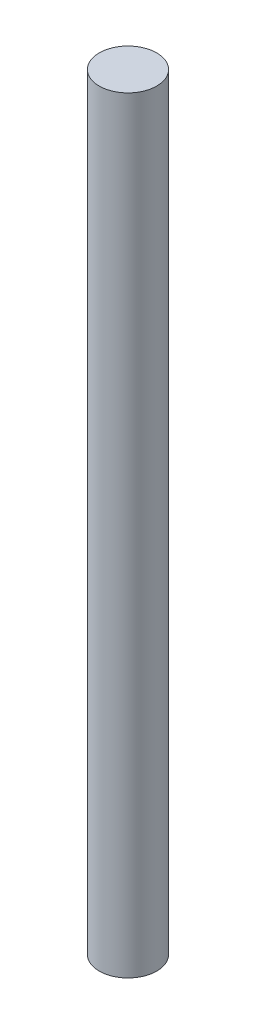
SolidWorks part; units mm, degrees
ref_plane "Front Plane" through (0, 0, 0) normal (0, 0, 1) x (1, 0, 0)
ref_plane "Top Plane" through (0, 0, 0) normal (0, 1, 0) x (1, 0, 0)
ref_plane "Right Plane" through (0, 0, 0) normal (1, 0, 0) x (0, 0, -1)
sketch "Sketch1" plane through (0, 0, 0) normal (0, 1, 0) x (1, 0, 0)
  circle A0 centre (0, 0) radius 7.5
  dimension "D1" = 15
extrude "Boss-Extrude1" add sketch "Sketch1" along normal blind 200
